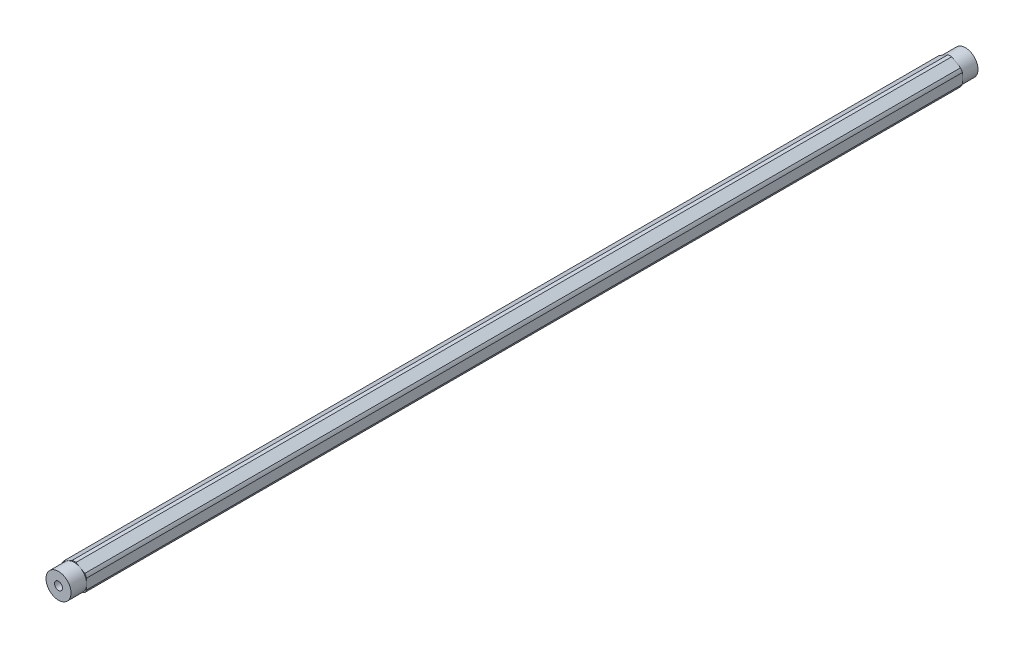
SolidWorks part; units mm, degrees
ref_plane "Front Plane" through (0, 0, 0) normal (0, 0, 1) x (1, 0, 0)
ref_plane "Top Plane" through (0, 0, 0) normal (0, 1, 0) x (1, 0, 0)
ref_plane "Right Plane" through (0, 0, 0) normal (1, 0, 0) x (0, 0, -1)
sketch "Sketch1" plane through (0, 0, 0) normal (0, 0, 1) x (1, 0, 0)
  line L1 (0, 7.3323) -> (-6.35, 3.6662)
  line L2 (-6.35, 3.6662) -> (-6.35, -3.6662)
  line L3 (-6.35, -3.6662) -> (0, -7.3323)
  line L4 (0, -7.3323) -> (6.35, -3.6662)
  line L5 (6.35, -3.6662) -> (6.35, 3.6662)
  line L6 (6.35, 3.6662) -> (0, 7.3323)
  circle A0 centre (0, 0) radius 6.35 construction
  circle A1 centre (0, 0) radius 6.858
  dimension "D1" = 12.7
  dimension "D2" = 13.716
extrude "Boss-Extrude1" add sketch "Sketch1" along normal mid plane 444.5
sketch "Sketch5" plane through (0, 0, 222.25) normal (0, 0, 1) x (1, 0, 0)
  circle A0 centre (0, 0) radius 6.35
  dimension "D1" = 12.7
extrude "Boss-Extrude2" add sketch "Sketch5" along normal blind 7.9375
hole_wizard "#10-32 Tapped Hole2" positions "3DSketch4" profile "Sketch6" tap size "#10-32" standard "ANSI Inch"
sketch3d "3DSketch4"
  line L0 (0, 0, 230.1875) -> (0, 0, 222.25) construction
  point P0 (0, 0, 230.1875)
sketch "Sketch6" plane through (0, 0, 230.1875) normal (1, 0, 0) x (0, -1, 0)
  line L0 (0, 0) -> (0, 16.2908)
  line L1 (0, 16.2908) -> (2.0193, 15.0774)
  line L2 (2.0193, 15.0774) -> (2.0193, 0)
  line L5 (2.0193, 0) -> (0, 0)
  line L10 (0, 16.2908) -> (-2.0193, 15.0774) construction
  line L11 (0, -6.35) -> (0, 107.95) construction
  dimension "Tap Drill Dia." = 4.0386
  dimension "Tap Drill Depth" = 15.0774
  dimension "Drill Angle" = 118
cosmetic thread "Hole Thread3" parameters "D1"=12.7, "D2"=4.826
mirror "Mirror1" about plane through (0, 0, 0) normal (0, 0, 1) of "#10-32 Tapped Hole2", "Boss-Extrude2"
cosmetic thread "Hole Thread4" parameters "D1"=12.7, "D2"=4.826
cosmetic thread "Hole Thread6" parameters "D1"=12.7, "D2"=4.826
